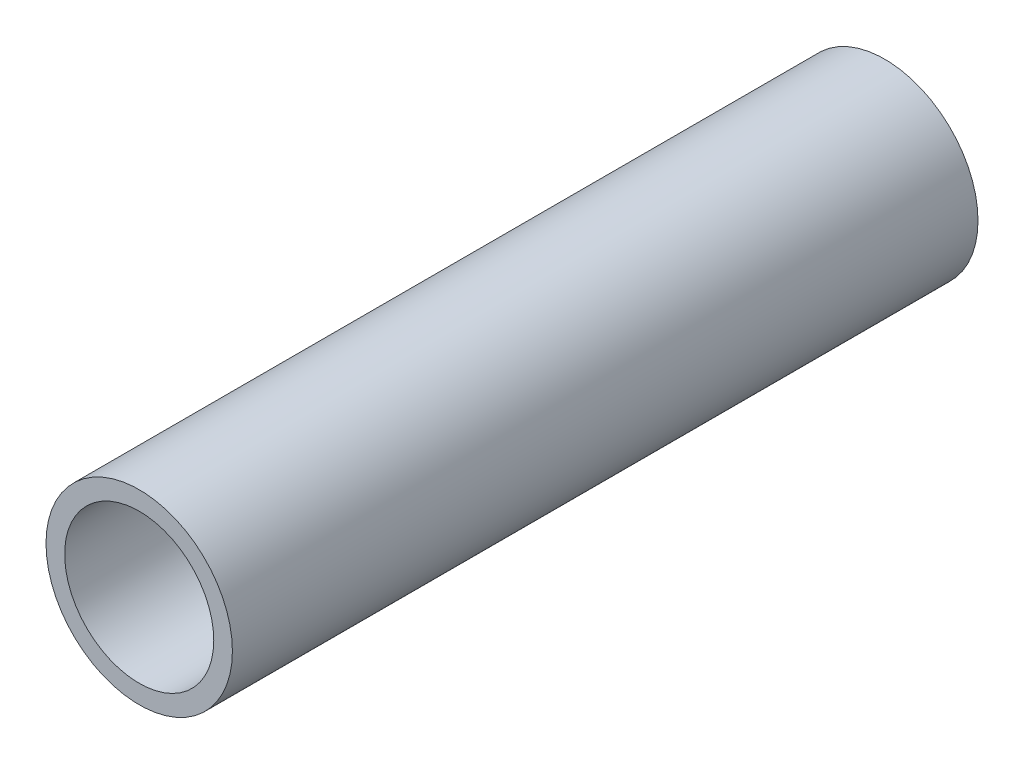
SolidWorks part; units mm, degrees
material "Thornel VCB-20 ｶｰﾎﾞﾝ ｸﾛｽ"
ref_plane "正面" through (0, 0, 0) normal (0, 0, 1) x (1, 0, 0)
ref_plane "平面" through (0, 0, 0) normal (0, 1, 0) x (1, 0, 0)
ref_plane "右側面" through (0, 0, 0) normal (1, 0, 0) x (0, 0, -1)
sketch "ｽｹｯﾁ1" plane through (0, 0, 0) normal (0, 0, 1) x (1, 0, 0)
  circle A0 centre (0, 0) radius 5
  circle A1 centre (0, 0) radius 4
  dimension "D1" = 10
  dimension "D2" = 8
extrude "ﾎﾞｽ - 押し出し1" add sketch "ｽｹｯﾁ1" along normal blind 40
equation "\"length\"= 40mm"
equation "\"D1@ﾎﾞｽ - 押し出し1\"=\"length\""
